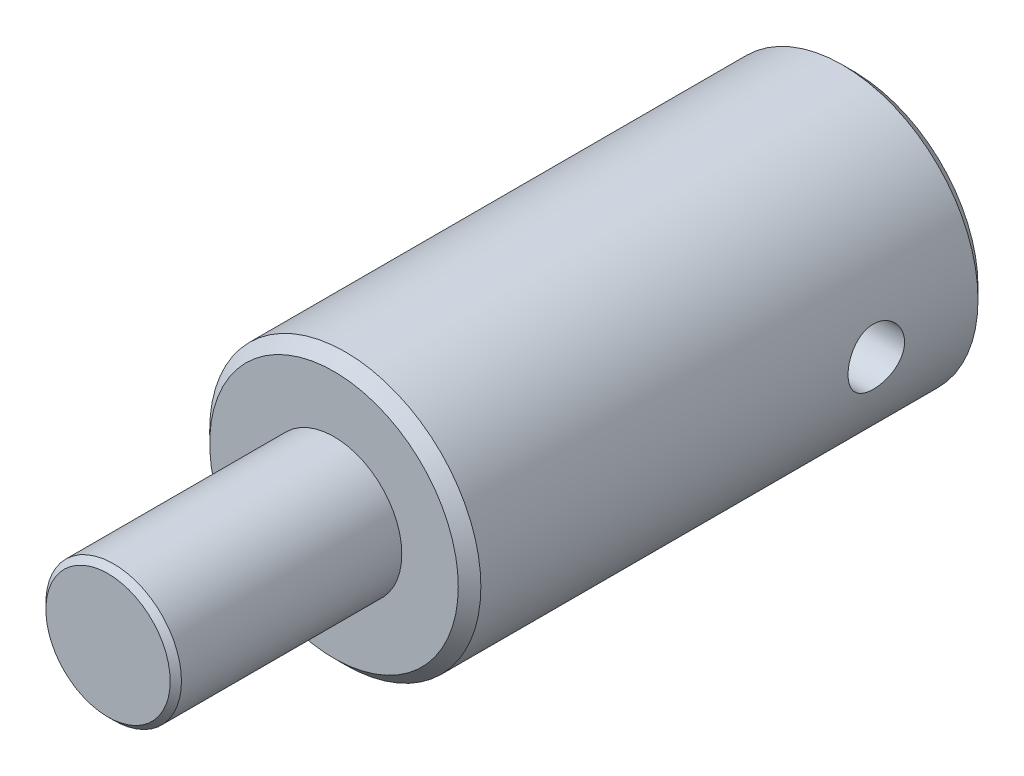
SolidWorks part; units mm, degrees
ref_plane "Front Plane" through (0, 0, 0) normal (0, 0, 1) x (1, 0, 0)
ref_plane "Top Plane" through (0, 0, 0) normal (0, 1, 0) x (1, 0, 0)
ref_plane "Right Plane" through (0, 0, 0) normal (1, 0, 0) x (0, 0, -1)
sketch "Sketch1" plane through (0, 0, 0) normal (0, 0, 1) x (1, 0, 0)
  circle A0 centre (0, 0) radius 6
  dimension "D1" = 12
extrude "Boss-Extrude1" add sketch "Sketch1" along normal blind 23
sketch "Sketch2" plane through (0, 0, 23) normal (0, 0, 1) x (1, 0, 0)
  circle A0 centre (0, 0) radius 3
  circle A1 centre (0, 0) radius 2
  point P5 (1.1968, -2.751)
  point P6 (0, 0)
  point P7 (0, 0.3437)
  dimension "D1" = 4
  dimension "D2" = 6
extrude "Boss-Extrude2" add sketch "Sketch2" along normal blind 10 contours A0 A1 | A0 A1
chamfer "Chamfer1" distance 0.5 angle 45 2 edges at (6, 0, 0) (6, 0, 23)
chamfer "Chamfer2" distance 0.25 angle 45 1 edges at (3, 0, 33)
sketch "Sketch4" plane through (0, 0, 0) normal (1, 0, 0) x (0, 0, -1)
  line L0 (-5, 0) -> (0, 0) construction
  circle A0 centre (-5, 0) radius 1.25
  dimension "D2" = 2.5
  dimension "D1" = 5
extrude "Cut-Extrude1" cut sketch "Sketch4" against normal through all both and the other way through all
